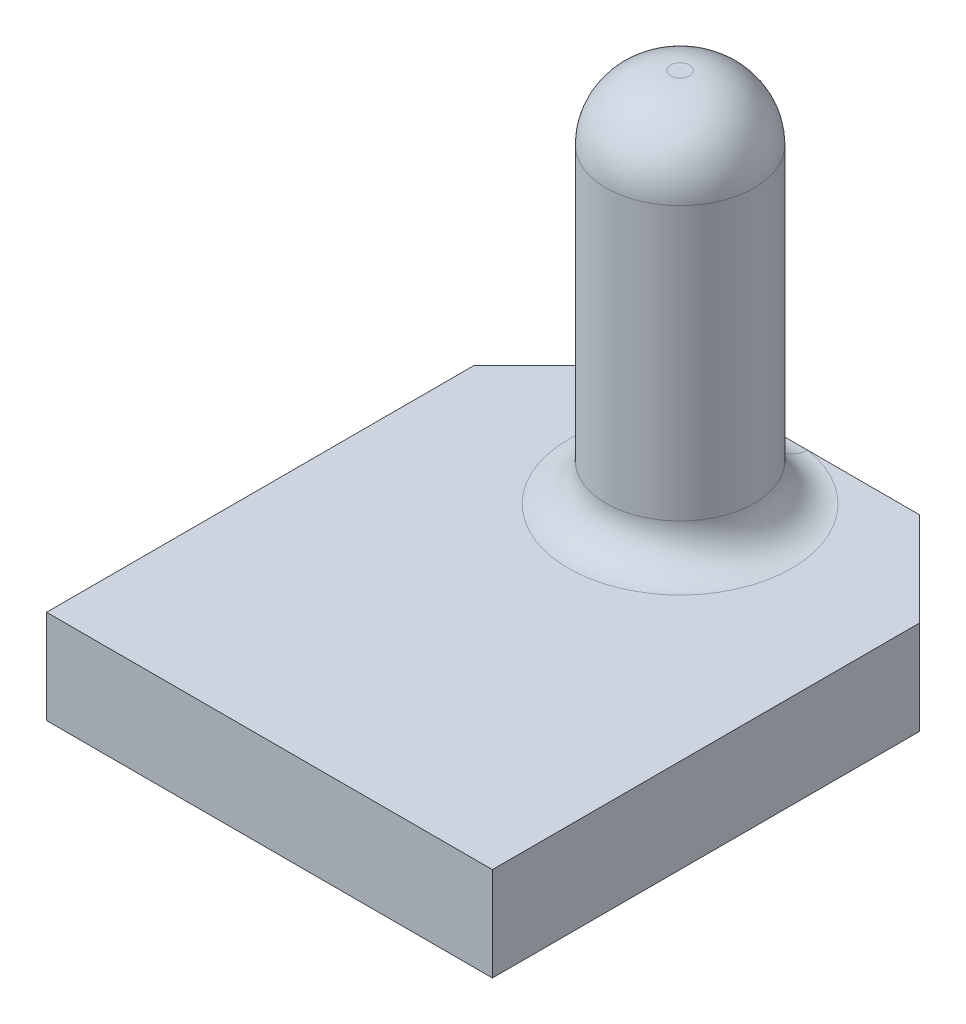
SolidWorks part; units mm, degrees
ref_plane "Front Plane" through (0, 0, 0) normal (0, 0, 1) x (1, 0, 0)
ref_plane "Top Plane" through (0, 0, 0) normal (0, 1, 0) x (1, 0, 0)
ref_plane "Right Plane" through (0, 0, 0) normal (1, 0, 0) x (0, 0, -1)
sketch "Sketch1" plane through (0, 0, 0) normal (0, 1, 0) x (1, 0, 0)
  line L1 (-11.875, -13.875) -> (11.875, -13.875)
  line L2 (-11.875, -13.875) -> (-11.875, 13.875)
  line L3 (-11.875, 13.875) -> (11.875, 13.875)
  line L4 (11.875, -13.875) -> (11.875, 13.875)
  line L5 (-11.875, -13.875) -> (11.875, 13.875) construction
  line L6 (-11.875, 13.875) -> (11.875, -13.875) construction
  point P0 (0, 0)
  dimension "D1" = 23.75
  dimension "D2" = 27.75
extrude "Boss-Extrude1" add sketch "Sketch1" along normal blind 5
sketch "Sketch2" plane through (0, 5, 0) normal (0, 1, 0) x (1, 0, 0)
  circle A0 centre (0, 8) radius 3.95
  dimension "D1" = 7.9
  dimension "D2" = 8
extrude "Boss-Extrude2" add sketch "Sketch2" along normal blind 20
fillet "Fillet1" radius 3.45 1 edges at (0, 25, -4.05)
fillet "Fillet2" radius 2 1 edges at (0, 5, -11.95)
chamfer "Chamfer1" distance 5 angle 45 2 edges at (-11.875, 2.5, -13.875) (11.875, 2.5, -13.875)
